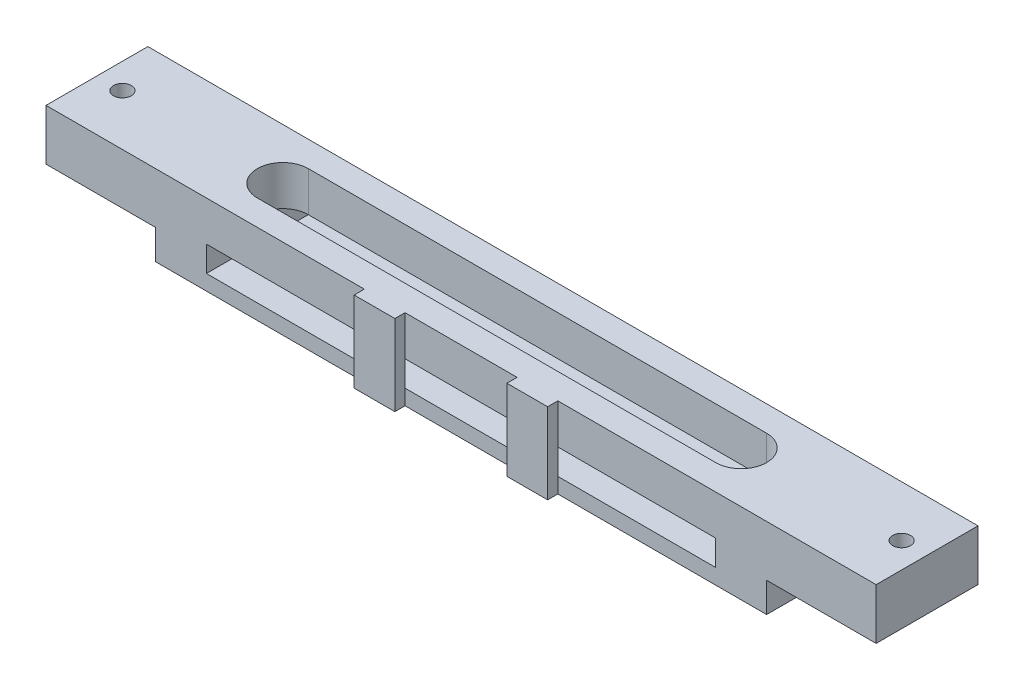
SolidWorks part; units mm, degrees
other "Markup1"
sketch "Sketch3" plane through (81.3, 22.34, 15) normal (0.0958, 0.2113, 0.9727) x (0.9922, -0.0986, -0.0763)
ref_plane "Front Plane" through (0, 0, 0) normal (0, 0, 1) x (1, 0, 0)
ref_plane "Top Plane" through (0, 0, 0) normal (0, 1, 0) x (1, 0, 0)
ref_plane "Right Plane" through (0, 0, 0) normal (1, 0, 0) x (0, 0, -1)
sketch "Sketch1" plane through (0, 0, 0) normal (0, 0, 1) x (1, 0, 0)
  line L16 (81.5, 0) -> (-81.5, 0)
  line L17 (-81.5, 0) -> (-81.5, 10)
  line L18 (-81.5, 10) -> (81.5, 10)
  line L22 (81.5, 0) -> (81.5, 10)
  point P0 (0, 0)
  dimension "D1" = 10
  dimension "D3" = 163
extrude "Boss-Extrude1" add sketch "Sketch1" along normal blind 20
sketch "Sketch2" plane through (0, 10, 0) normal (0, 1, 0) x (1, 0, 0)
  line L1 (-81.5, -20) -> (-81.5, 0) construction
  line L3 (-81.5, -10) -> (-76.5, -10) construction
  line L4 (76.5, -10) -> (81.5, -10) construction
  line L6 (81.5, -20) -> (81.5, 0) construction
  circle A1 centre (-76.5, -10) radius 1.75
  circle A2 centre (76.5, -10) radius 1.75
  point P8 (-81.5, -10)
  point P16 (81.5, -10)
  dimension "D1" = 3.5
  dimension "D3" = 5
sketch "Sketch4" plane through (0, 0, 0) normal (0, -1, 0) x (1, 0, 0)
  line L0 (-45, 10) -> (45, 10) construction
  line L1 (-60, 20) -> (60, 20)
  line L2 (-60, 20) -> (-60, 0)
  line L3 (-60, 0) -> (60, 0)
  line L4 (60, 20) -> (60, 0)
  line L5 (-60, 20) -> (60, 0) construction
  line L6 (-60, 0) -> (60, 20) construction
  line L16 (-81.5, 20) -> (-81.5, 0) construction
  line L17 (-81.5, 20) -> (81.5, 20) construction
  line L23 (-45, 12.35) -> (45, 12.35)
  line L24 (-45, 7.65) -> (45, 7.65)
  arc A14 (-45, 12.35) -> (-45, 7.65) centre (-45, 10) ccw
  arc A15 (45, 7.65) -> (45, 12.35) centre (45, 10) ccw
  point P7 (0, 10)
  point P14 (0, 10)
  point P19 (0, 0)
  point P25 (-81.5, 10)
  point P28 (-60, 10)
  dimension "D1" = 120
  dimension "D3" = 2.35
  dimension "D4" = 90
extrude "Boss-Extrude2" add sketch "Sketch4" along normal blind 5.84
sketch "Sketch5" plane through (0, 0, 20) normal (0, 0, 1) x (1, 0, 0)
  line L0 (60, -5.84) -> (-60, -5.84) construction
  line L6 (60, -5.84) -> (60, 0) construction
  line L7 (-50, 2.16) -> (50, 2.16)
  line L8 (-50, 2.16) -> (-50, -2.84)
  line L9 (-50, -2.84) -> (50, -2.84)
  line L10 (50, 2.16) -> (50, -2.84)
  dimension "D1" = 3
  dimension "D2" = 5
  dimension "D3" = 100
  dimension "D4" = 10
extrude "Cut-Extrude1" cut sketch "Sketch5" against normal up to surface (20 mm away) up to face at (0, 1.04, 0)
sketch "Sketch6" plane through (0, 2.16, 0) normal (0, -1, 0) x (1, 0, 0)
  line L0 (-45, 7.65) -> (45, 7.65) construction
  line L3 (45, 12.35) -> (-45, 12.35) construction
  line L6 (-45, 5) -> (45, 5)
  line L7 (45, 15) -> (-45, 15)
  line L9 (-45, 7.65) -> (45, 7.65) construction
  line L10 (45, 12.35) -> (-45, 12.35) construction
  arc A4 (45, 7.65) -> (45, 12.35) centre (45, 10) ccw construction
  arc A6 (-45, 12.35) -> (-45, 7.65) centre (-45, 10) ccw construction
  arc A8 (-45, 12.35) -> (-45, 7.65) centre (-45, 10) ccw construction
  arc A9 (45, 7.65) -> (45, 12.35) centre (45, 10) ccw construction
  arc A10 (45, 5) -> (45, 15) centre (45, 10) ccw
  arc A11 (-45, 15) -> (-45, 5) centre (-45, 10) ccw
  dimension "D1" = 5
extrude "Cut-Extrude2" cut sketch "Sketch6" against normal blind 10
extrude "Cut-Extrude3" cut sketch "Sketch2" against normal through all both and the other way through all contours A2 | A1
sketch "Sketch7" plane through (0, 0, 20) normal (0, 0, 1) x (1, 0, 0)
  line L6 (81.5, 10) -> (-81.5, 10) construction
  line L7 (-19, 10) -> (-11, 10)
  line L8 (-19, 10) -> (-19, -5.84)
  line L9 (-19, -5.84) -> (-11, -5.84)
  line L10 (-11, 10) -> (-11, -5.84)
  line L11 (60, -5.84) -> (-60, -5.84) construction
  line L12 (-15, 10) -> (15, 10) construction
  line L13 (11, 10) -> (19, 10)
  line L14 (11, 10) -> (11, -5.84)
  line L15 (11, -5.84) -> (19, -5.84)
  line L16 (19, 10) -> (19, -5.84)
  point P15 (0, 10)
  dimension "D1" = 8
  dimension "D2" = 8
  dimension "D3" = 30
extrude "Boss-Extrude3" add sketch "Sketch7" along normal blind 2
